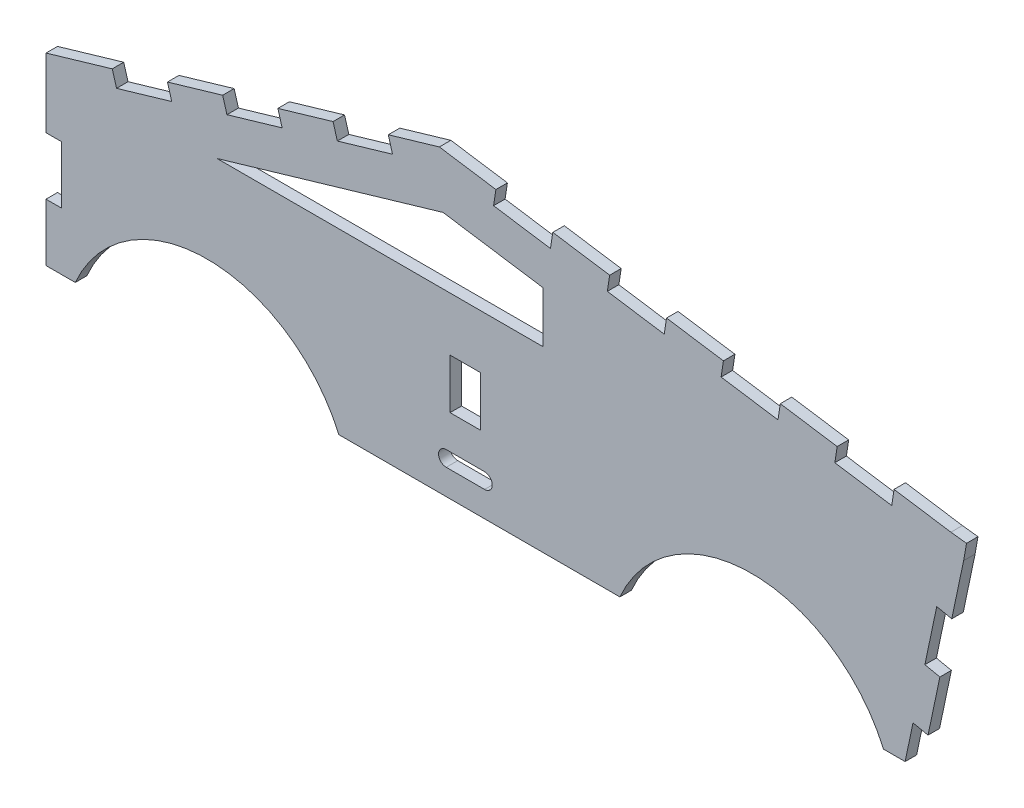
SolidWorks part; units mm, degrees
ref_plane "Front Plane" through (0, 0, 0) normal (0, 0, 1) x (1, 0, 0)
ref_plane "Top Plane" through (0, 0, 0) normal (0, 1, 0) x (1, 0, 0)
ref_plane "Right Plane" through (0, 0, 0) normal (1, 0, 0) x (0, 0, -1)
sketch "Sketch1" plane through (0, 0, 0) normal (0, 0, 1) x (1, 0, 0)
  line L0 (0, 0) -> (-220, 0)
  line L1 (-220, 0) -> (-220, 45)
  line L2 (-220, 45) -> (-121.163, 73.9869)
  line L3 (-121.163, 73.9869) -> (11.337, 53.8189)
  line L4 (11.337, 53.8189) -> (0, 0)
  line L5 (-179.4092, 46.4833) -> (-120.476, 63.7672)
  line L6 (-120.476, 63.7672) -> (-94.4092, 59.7995)
  line L7 (-179.4092, 46.4833) -> (-94.4092, 46.4833)
  line L8 (-94.4092, 46.4833) -> (-94.4092, 59.7995)
  line L9 (-217.1857, 35.4042) -> (-120.476, 63.7672) construction
  line L10 (9.2725, 44.018) -> (9.8322, 43.9327)
  line L11 (-120.476, 63.7672) -> (9.8322, 43.9327) construction
  dimension "D1" = 220
  dimension "D2" = 45
  dimension "D3" = 155
  dimension "D4" = 103
  dimension "D5" = 132.5
  dimension "D6" = 55
  dimension "D8" = 85
  dimension "D7" = 10
extrude "Boss-Extrude1" add sketch "Sketch1" against normal blind 3 contours L4 L3 L2 L1 L0 L8 L7 L5 L6
sketch "Sketch2" plane through (0, 0, 0) normal (0, 0, 1) x (1, 0, 0)
  line L0 (0, 0) -> (-220, 0) construction
  line L1 (-220, 0) -> (-220, 45) construction
  circle A0 centre (-182, -15) radius 37.5
  circle A1 centre (-40, -15) radius 37.5
  dimension "D3" = 75
  dimension "D5" = 75
  dimension "D1" = 15
  dimension "D2" = 38
  dimension "D4" = 40
  dimension "D6" = 15
extrude "Cut-Extrude1" cut sketch "Sketch2" against normal blind 3
sketch "Sketch3" plane through (0, 0, 0) normal (0, 0, 1) x (1, 0, 0)
  line L0 (-206.732, 53.0597) -> (-205.6063, 49.2214)
  line L1 (-220, 45) -> (-121.163, 73.9869) construction
  line L2 (-192.3382, 57.2811) -> (-191.2125, 53.4428)
  line L5 (-121.4377, 78.0748) -> (11.9389, 57.7733)
  line L6 (-221.1257, 48.8383) -> (-121.4377, 78.0748)
  line L7 (-121.4377, 78.0748) -> (-106.6946, 75.8307)
  line L8 (-221.1257, 48.8383) -> (-206.732, 53.0597)
  line L9 (-77.0363, 71.3164) -> (-77.6382, 67.3619)
  line L10 (-121.163, 73.9869) -> (11.337, 53.8189) construction
  line L11 (-3.4922, 56.0761) -> (-2.8903, 60.0305)
  line L12 (-18.3214, 58.3332) -> (-17.7195, 62.2877)
  line L13 (-177.9445, 61.5025) -> (-176.8188, 57.6642)
  line L14 (-163.5507, 65.7239) -> (-162.425, 61.8856)
  line L15 (-149.157, 69.9453) -> (-148.0313, 66.107)
  line L16 (-133.6375, 70.3284) -> (-134.7632, 74.1667)
  line L17 (-220, 45) -> (-205.6063, 49.2214)
  line L18 (-192.3382, 57.2811) -> (-177.9445, 61.5025)
  line L19 (-191.2125, 53.4428) -> (-176.8188, 57.6642)
  line L20 (-163.5507, 65.7239) -> (-149.157, 69.9453)
  line L21 (-162.425, 61.8856) -> (-148.0313, 66.107)
  line L22 (-134.7632, 74.1667) -> (-121.4377, 78.0748)
  line L23 (-133.6375, 70.3284) -> (-121.163, 73.9869)
  line L24 (-33.1506, 60.5904) -> (-32.5487, 64.5449)
  line L25 (-47.9798, 62.8476) -> (-47.3779, 66.802)
  line L26 (-62.809, 65.1048) -> (-62.2071, 69.0592)
  line L27 (-92.4674, 69.6191) -> (-91.8655, 73.5736)
  line L28 (-107.2966, 71.8763) -> (-106.6946, 75.8307)
  line L29 (11.337, 53.8189) -> (-3.4922, 56.0761)
  line L30 (-2.8903, 60.0305) -> (11.9389, 57.7733)
  line L31 (-18.3214, 58.3332) -> (-33.1506, 60.5904)
  line L32 (-32.5487, 64.5449) -> (-17.7195, 62.2877)
  line L33 (-47.9798, 62.8476) -> (-62.809, 65.1048)
  line L34 (-62.2071, 69.0592) -> (-47.3779, 66.802)
  line L35 (-77.6382, 67.3619) -> (-92.4674, 69.6191)
  line L36 (-91.8655, 73.5736) -> (-77.0363, 71.3164)
  line L37 (-107.2966, 71.8763) -> (-121.163, 73.9869)
  line L39 (-221.1257, 48.8383) -> (-224, 47.9954)
  line L45 (-224, 47.9954) -> (-224, 45)
  line L46 (-224, 0) -> (-220, 0)
  line L49 (-220, 30) -> (-224, 30)
  line L50 (-224, 0) -> (-224, 45)
  line L51 (-224, 0) -> (-224, 15)
  line L52 (11.9389, 57.7733) -> (16.0031, 57.298)
  line L55 (16.0031, 57.298) -> (15.2511, 52.9944)
  line L56 (-220, 0) -> (-220, 45) construction
  line L57 (-220, 15) -> (-224, 15)
  line L58 (-220, 45) -> (-220, 30)
  line L59 (-224, 30) -> (-224, 45)
  line L60 (-220, 15) -> (-220, 0)
  line L61 (8.2451, 39.141) -> (12.1592, 38.3165)
  line L62 (15.2511, 52.9944) -> (3.9141, -0.8245)
  line L63 (15.2511, 52.9944) -> (12.1592, 38.3165)
  line L64 (11.337, 53.8189) -> (0, 0) construction
  line L65 (5.1532, 24.4631) -> (9.0673, 23.6386)
  line L66 (2.0613, 9.7853) -> (5.9754, 8.9607)
  line L67 (11.337, 53.8189) -> (8.2451, 39.141)
  line L68 (9.0673, 23.6386) -> (5.9754, 8.9607)
  line L69 (5.1532, 24.4631) -> (2.0613, 9.7853)
  dimension "D3" = 15
  dimension "D4" = 15
  dimension "D5" = 15
  dimension "D6" = 15
  dimension "D7" = 15
  dimension "D8" = 4
  dimension "D9" = 15
  dimension "D10" = 15
  dimension "D11" = 15
  dimension "D12" = 15
  dimension "D13" = 15
  dimension "D14" = 15
  dimension "D15" = 15
  dimension "D18" = 86.76
  dimension "D19" = 15
  dimension "D20" = 15
  dimension "D21" = 15
  dimension "D22" = 15
  dimension "D1" = 4
  dimension "D16" = 4
extrude "Boss-Extrude4" add sketch "Sketch3" against normal blind 3
sketch "Sketch4" plane through (0, 0, 0) normal (0, 0, 1) x (1, 0, 0)
  line L1 (-118.6478, 32.4726) -> (-110.6478, 32.4726)
  line L2 (-118.6478, 32.4726) -> (-118.6478, 19.4726)
  line L3 (-118.6478, 19.4726) -> (-110.6478, 19.4726)
  line L4 (-110.6478, 32.4726) -> (-110.6478, 19.4726)
  dimension "D1" = 8
  dimension "D2" = 13
extrude "Cut-Extrude2" cut sketch "Sketch4" against normal blind 10
sketch "Sketch5" plane through (0, 0, 0) normal (0, 0, 1) x (1, 0, 0)
  line L0 (-119.6478, 8.6352) -> (-109.6478, 8.6352) construction
  line L1 (-119.6478, 10.6352) -> (-109.6478, 10.6352)
  line L2 (-119.6478, 6.6352) -> (-109.6478, 6.6352)
  line L3 (-114.6478, 19.4726) -> (-114.6478, 8.6352) construction
  line L4 (-118.6478, 19.4726) -> (-110.6478, 19.4726) construction
  arc A0 (-119.6478, 10.6352) -> (-119.6478, 6.6352) centre (-119.6478, 8.6352) ccw
  arc A1 (-109.6478, 6.6352) -> (-109.6478, 10.6352) centre (-109.6478, 8.6352) ccw
  point P2 (-114.6478, 8.6352)
  dimension "D2" = 2
  dimension "D1" = 10
extrude "Cut-Extrude3" cut sketch "Sketch5" against normal blind 10
